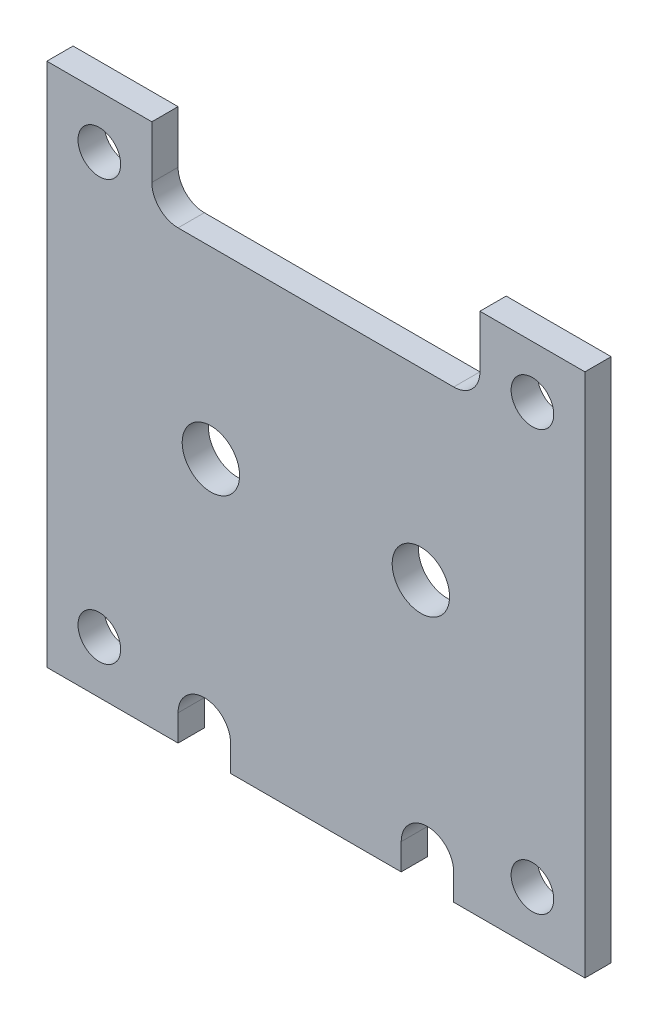
SolidWorks part; units mm, degrees
ref_plane "Front" through (0, 0, 0) normal (0, 0, 1) x (1, 0, 0)
ref_plane "Top" through (0, 0, 0) normal (0, 1, 0) x (1, 0, 0)
ref_plane "Right" through (0, 0, 0) normal (1, 0, 0) x (0, 0, -1)
sketch "Sketch1" plane through (0, 0, 0) normal (0, 0, 1) x (1, 0, 0)
  line L1 (-65.0875, -63.5) -> (65.0875, -63.5)
  line L2 (-65.0875, -63.5) -> (-65.0875, 63.5)
  line L3 (-65.0875, 63.5) -> (65.0875, 63.5)
  line L4 (65.0875, -63.5) -> (65.0875, 63.5)
  line L5 (-65.0875, -63.5) -> (65.0875, 63.5) construction
  line L6 (-65.0875, 63.5) -> (65.0875, -63.5) construction
  point P0 (0, 0)
  dimension "D1" = 130.175
  dimension "D2" = 127
extrude "Extrude1" add sketch "Sketch1" against normal blind 6.35
hole_wizard "3/8 Clearance Hole1" positions "Sketch3" profile "Sketch2" hole size "3/8" standard "Ansi Inch" end condition through all
sketch "Sketch3" plane through (0, 0, 0) normal (0, 0, 1) x (1, 0, 0)
  line L1 (-52.3875, -50.8) -> (52.3875, -50.8)
  line L2 (-52.3875, -50.8) -> (-52.3875, 50.8)
  line L3 (-52.3875, 50.8) -> (52.3875, 50.8)
  line L4 (52.3875, -50.8) -> (52.3875, 50.8)
  line L5 (-52.3875, -50.8) -> (52.3875, 50.8) construction
  line L6 (-52.3875, 50.8) -> (52.3875, -50.8) construction
  point P0 (-52.3875, 50.8)
  point P1 (52.3875, 50.8)
  point P3 (52.3875, -50.8)
  point P5 (-52.3875, -50.8)
  dimension "D1" = 104.775
  dimension "D2" = 101.6
sketch "Sketch2" plane through (-52.3875, 50.8, 0) normal (1, 0, 0) x (0, -1, 0)
  line L0 (0, 0) -> (0, 6.35)
  line L1 (0, 6.35) -> (5.1587, 6.35)
  line L2 (5.1587, 6.35) -> (5.1587, 0)
  line L5 (5.1587, 0) -> (0, 0)
  line L11 (0, -6.35) -> (0, 107.95) construction
  dimension "Thru Hole Dia." = 10.3175
  dimension "Thru Hole Depth" = 6.35
sketch "Sketch4" plane through (0, 0, 0) normal (0, 0, 1) x (1, 0, 0)
  line L0 (65.0875, 63.5) -> (-65.0875, 63.5) construction
  line L1 (-39.6875, 63.5) -> (39.6875, 63.5)
  line L2 (-39.6875, 63.5) -> (-39.6875, 44.45)
  line L3 (-39.6875, 44.45) -> (39.6875, 44.45)
  line L4 (39.6875, 63.5) -> (39.6875, 44.45)
  circle A0 centre (-52.3875, 50.8) radius 5.1587 construction
  circle A1 centre (52.3875, 50.8) radius 5.1587 construction
  dimension "D1" = 12.7
  dimension "D2" = 12.7
  dimension "D3" = 19.05
extrude "Extrude2" cut sketch "Sketch4" against normal through all
fillet "Fillet2" radius 6.35 2 edges at (39.6875, 44.45, -3.175) (-39.6875, 44.45, -3.175)
sketch "Sketch5" plane through (0, 0, -6.35) normal (0, 0, -1) x (-1, 0, 0)
  line L0 (65.0875, -63.5) -> (-65.0875, -63.5) construction
  line L1 (-33.3375, -63.5) -> (-20.6375, -63.5)
  line L2 (-33.3375, -63.5) -> (-33.3375, -57.15)
  line L3 (-33.3375, -57.15) -> (-20.6375, -57.15)
  line L4 (-20.6375, -63.5) -> (-20.6375, -57.15)
  line L5 (-26.9875, -57.15) -> (-26.9875, -63.5) construction
  line L6 (-65.0875, -63.5) -> (-65.0875, 63.5) construction
  dimension "D1" = 12.7
  dimension "D2" = 6.35
  dimension "D3" = 38.1
extrude "Extrude3" cut sketch "Sketch5" against normal through all
sketch "Sketch6" plane through (0, 0, -6.35) normal (0, 0, -1) x (-1, 0, 0)
  line L1 (-20.6375, -57.15) -> (-33.3375, -57.15) construction
  circle A0 centre (-26.9875, -57.15) radius 6.35
extrude "Extrude4" cut sketch "Sketch6" against normal through all
mirror "Mirror2" about plane through (0, 0, 0) normal (1, 0, 0) of "Extrude4", "Extrude3"
hole_wizard "1/2 Clearance Hole1" positions "Sketch8" profile "Sketch7" hole size "1/2" standard "Ansi Inch" end condition through all
sketch "Sketch8" plane through (0, 0, -6.35) normal (0, 0, -1) x (-1, 0, 0)
  line L0 (-25.4, 0) -> (25.4, 0) construction
  point P0 (-25.4, 0)
  point P1 (25.4, 0)
  dimension "D1" = 50.8
sketch "Sketch7" plane through (25.4, 0, -6.35) normal (1, 0, 0) x (0, 1, 0)
  line L0 (0, 0) -> (0, 6.35)
  line L1 (0, 6.35) -> (6.9456, 6.35)
  line L2 (6.9456, 6.35) -> (6.9456, 0)
  line L5 (6.9456, 0) -> (0, 0)
  line L11 (0, -6.35) -> (0, 107.95) construction
  dimension "Thru Hole Dia." = 13.8913
  dimension "Thru Hole Depth" = 6.35
